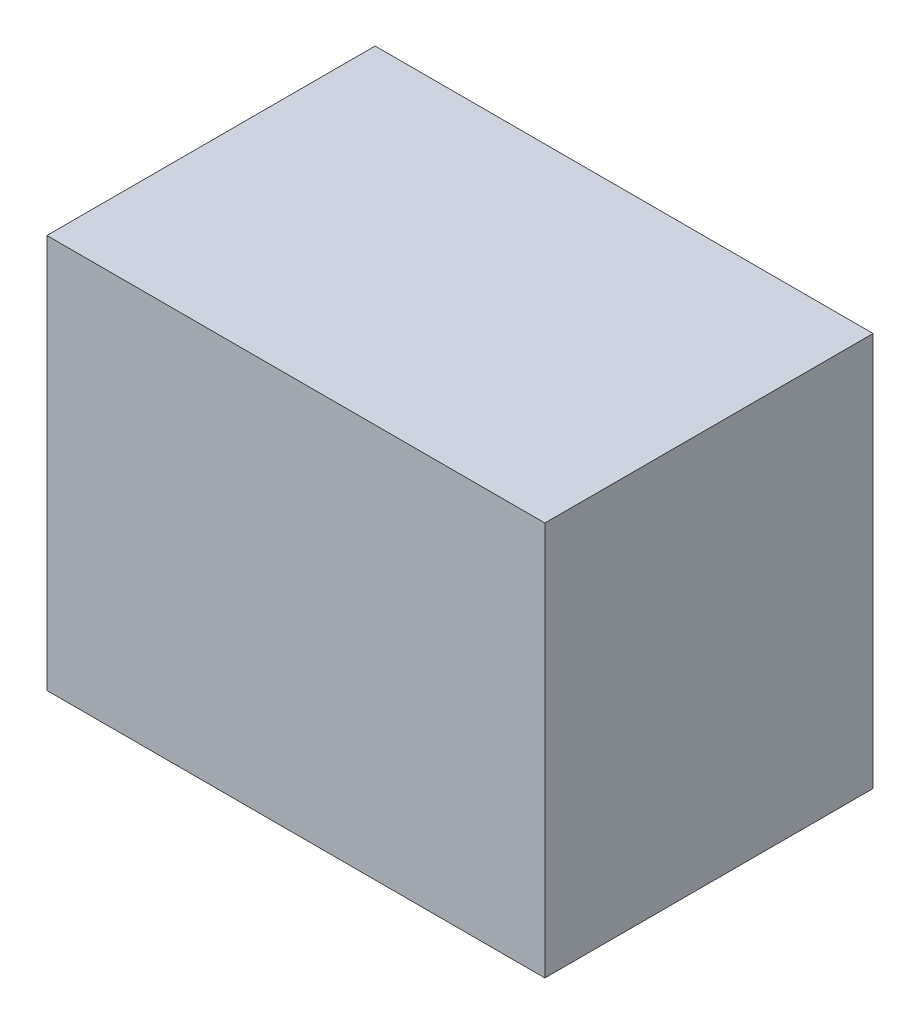
SolidWorks part; units mm, degrees
ref_plane "Front Plane" through (0, 0, 0) normal (0, 0, 1) x (1, 0, 0)
ref_plane "Top Plane" through (0, 0, 0) normal (0, 1, 0) x (1, 0, 0)
ref_plane "Right Plane" through (0, 0, 0) normal (1, 0, 0) x (0, 0, -1)
sketch "Sketch1" plane through (0, 0, 0) normal (0, 0, 1) x (1, 0, 0)
  line L0 (0, 0) -> (48.4, 0)
  line L1 (48.4, 0) -> (48.4, 38.3)
  line L2 (48.4, 38.3) -> (0, 38.3)
  line L3 (0, 38.3) -> (0, 0)
  dimension "D1" = 38.3
  dimension "D2" = 48.4
extrude "Boss-Extrude1" add sketch "Sketch1" along normal blind 31.9
